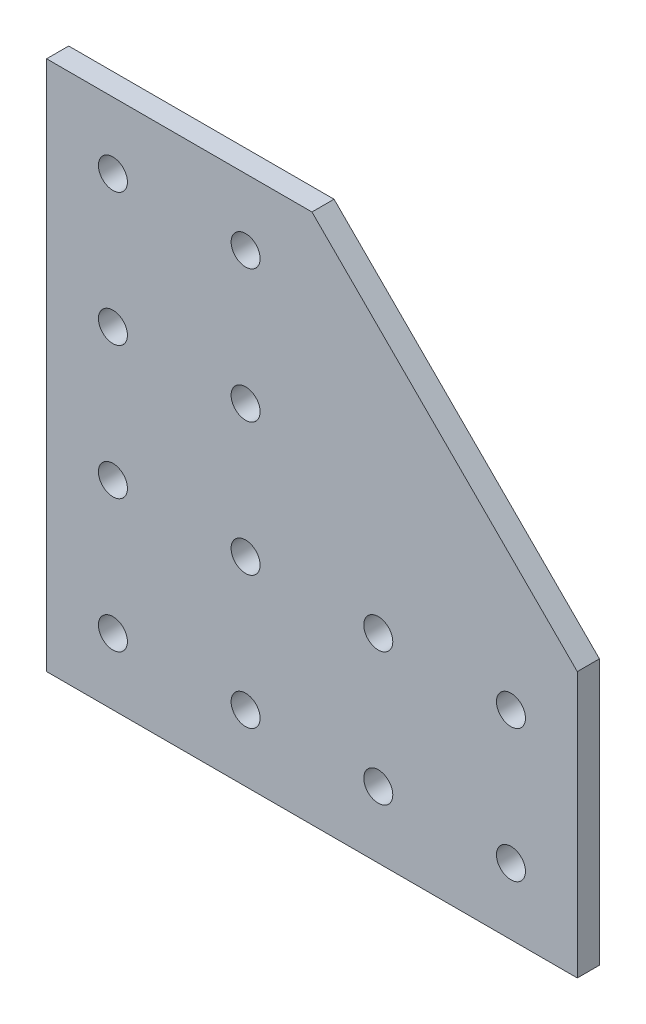
SolidWorks part; units mm, degrees
material "6061 Alloy"
ref_plane "Front Plane" through (0, 0, 0) normal (0, 0, 1) x (1, 0, 0)
ref_plane "Top Plane" through (0, 0, 0) normal (0, 1, 0) x (1, 0, 0)
ref_plane "Right Plane" through (0, 0, 0) normal (1, 0, 0) x (0, 0, -1)
sketch "Sketch1" plane through (0, 0, 0) normal (0, 0, 1) x (1, 0, 0)
  line L0 (0, 0) -> (0, 152.4)
  line L1 (19.05, 19.05) -> (57.15, 19.05) construction
  line L2 (57.15, 19.05) -> (95.25, 19.05) construction
  line L3 (19.05, 19.05) -> (19.05, 57.15) construction
  line L4 (152.4, 76.2) -> (76.2, 152.4)
  line L5 (152.4, 0) -> (0, 0)
  line L6 (19.05, 57.15) -> (19.05, 95.25) construction
  line L7 (152.4, 76.2) -> (152.4, 0)
  line L8 (0, 152.4) -> (76.2, 152.4)
  line L9 (95.25, 19.05) -> (133.35, 19.05) construction
  line L10 (133.35, 19.05) -> (133.35, 57.15) construction
  line L11 (133.35, 57.15) -> (95.25, 57.15) construction
  line L12 (95.25, 57.15) -> (95.25, 19.05) construction
  line L13 (95.25, 57.15) -> (57.15, 57.15) construction
  line L14 (57.15, 57.15) -> (57.15, 19.05) construction
  line L15 (57.15, 57.15) -> (19.05, 57.15) construction
  line L16 (19.05, 95.25) -> (19.05, 133.35) construction
  line L17 (19.05, 133.35) -> (57.15, 133.35) construction
  line L18 (57.15, 133.35) -> (57.15, 95.25) construction
  line L19 (57.15, 95.25) -> (57.15, 57.15) construction
  line L20 (57.15, 95.25) -> (19.05, 95.25) construction
  circle A0 centre (19.05, 19.05) radius 4.1656
  circle A1 centre (57.15, 19.05) radius 4.1656
  circle A2 centre (95.25, 19.05) radius 4.1656
  circle A3 centre (19.05, 57.15) radius 4.1656
  circle A4 centre (19.05, 95.25) radius 4.1656
  circle A5 centre (133.35, 19.05) radius 4.1656
  circle A6 centre (133.35, 57.15) radius 4.1656
  circle A7 centre (95.25, 57.15) radius 4.1656
  circle A8 centre (57.15, 57.15) radius 4.1656
  circle A9 centre (19.05, 133.35) radius 4.1656
  circle A10 centre (57.15, 133.35) radius 4.1656
  circle A11 centre (57.15, 95.25) radius 4.1656
  dimension "D1" = 38.1
  dimension "E" = 8.3312
  dimension "D2" = 19.05
  dimension "C" = 76.2
  dimension "D3" = 19.05
  dimension "B" = 152.4
extrude "Boss-Extrude1" add sketch "Sketch1" along normal mid plane 6.35
